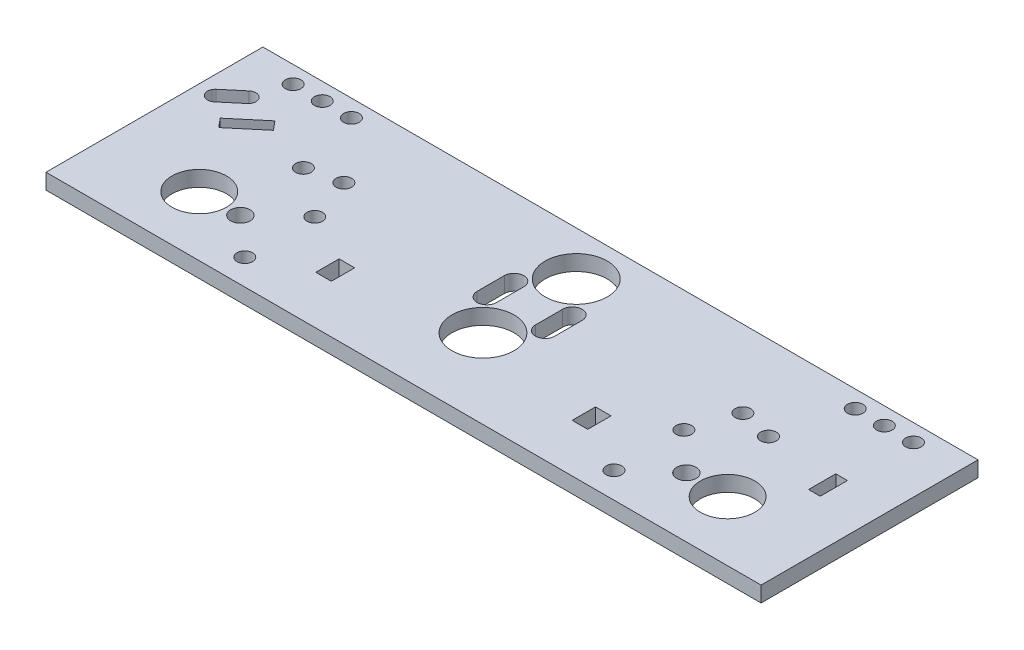
SolidWorks part; units mm, degrees
ref_plane "Front Plane" through (0, 0, 0) normal (0, 0, 1) x (1, 0, 0)
ref_plane "Top Plane" through (0, 0, 0) normal (0, 1, 0) x (1, 0, 0)
ref_plane "Right Plane" through (0, 0, 0) normal (1, 0, 0) x (0, 0, -1)
sketch "Sketch1" plane through (0, 0, 0) normal (0, 1, 0) x (1, 0, 0)
  line L0 (0, 0) -> (0, 59.0825) construction
  line L1 (-7.5, 15.5) -> (-7.5, 8.5) construction
  line L2 (-5, 15.5) -> (-5, 8.5)
  line L3 (-10, 15.5) -> (-10, 8.5)
  line L4 (-7.5, 15.5) -> (-7.5, 24) construction
  line L5 (-7.5, 8.5) -> (-7.5, 0) construction
  line L6 (-92.0307, 35.3895) -> (-92.0307, -20.4445)
  line L7 (-35, -2.0315) -> (-31, -2.0315)
  line L8 (-35, -2.0315) -> (-35, -8.0315)
  line L9 (-35, -8.0315) -> (-31, -8.0315)
  line L10 (-31, -2.0315) -> (-31, -8.0315)
  line L11 (-92.0307, -20.4445) -> (92.0307, -20.4445)
  line L12 (-92.0307, 35.3895) -> (92.0307, 35.3895)
  line L13 (7.5, 15.5) -> (7.5, 8.5) construction
  line L14 (5, 15.5) -> (5, 8.5)
  line L15 (10, 15.5) -> (10, 8.5)
  line L16 (7.5, 8.5) -> (7.5, 0) construction
  line L17 (7.5, 15.5) -> (7.5, 24) construction
  line L18 (31, -2.0315) -> (31, -8.0315)
  line L19 (35, -8.0315) -> (31, -8.0315)
  line L20 (35, -2.0315) -> (35, -8.0315)
  line L21 (35, -2.0315) -> (31, -2.0315)
  line L22 (92.0307, 35.3895) -> (92.0307, -20.4445)
  line L23 (-97.3653, 12) -> (-74.7906, 12) construction
  line L24 (76.8419, 13.9685) -> (79.8419, 13.9685)
  line L25 (76.8419, 13.9685) -> (76.8419, 6.9685)
  line L26 (76.8419, 6.9685) -> (79.8419, 6.9685)
  line L27 (79.8419, 13.9685) -> (79.8419, 6.9685)
  line L28 (-72.0903, 18.1667) -> (-74.0187, 20.4648)
  line L29 (-72.0903, 18.1667) -> (-79.7508, 11.7388)
  line L30 (-79.7508, 11.7388) -> (-81.6791, 14.0369)
  line L31 (-74.0187, 20.4648) -> (-81.6791, 14.0369)
  line L32 (-87.3337, 18.43) -> (-82.7374, 22.2868) construction
  line L33 (-88.6193, 19.9621) -> (-84.023, 23.8189)
  line L34 (-86.0481, 16.898) -> (-81.4519, 20.7547)
  circle A0 centre (0, 24) radius 8
  circle A1 centre (0, 0) radius 8
  arc A2 (-5, 15.5) -> (-10, 15.5) centre (-7.5, 15.5) ccw
  arc A3 (-10, 8.5) -> (-5, 8.5) centre (-7.5, 8.5) ccw
  circle A4 centre (-57.4, -5.0315) radius 2.5
  circle A5 centre (-47.5079, -13.7966) radius 2
  circle A6 centre (-47.5079, 4.2034) radius 2
  circle A7 centre (-59.8623, 13.6321) radius 2
  circle A8 centre (-64.8419, 30.9685) radius 2
  circle A9 centre (-72.3419, 30.9685) radius 2
  circle A10 centre (-79.8419, 30.9685) radius 2
  circle A11 centre (-68, -5.0315) radius 7
  circle A12 centre (-51.3496, 15.5457) radius 2
  arc A13 (5, 15.5) -> (10, 15.5) centre (7.5, 15.5) cw
  arc A14 (10, 8.5) -> (5, 8.5) centre (7.5, 8.5) cw
  circle A15 centre (51.3496, 15.5457) radius 2
  circle A16 centre (68, -5.0315) radius 7
  circle A17 centre (79.8419, 30.9685) radius 2
  circle A18 centre (72.3419, 30.9685) radius 2
  circle A19 centre (64.8419, 30.9685) radius 2
  circle A20 centre (59.8623, 13.6321) radius 2
  circle A21 centre (47.5079, 4.2034) radius 2
  circle A22 centre (47.5079, -13.7966) radius 2
  circle A23 centre (57.4, -5.0315) radius 2.5
  arc A24 (-88.6193, 19.9621) -> (-86.0481, 16.898) centre (-87.3337, 18.43) ccw
  arc A25 (-81.4519, 20.7547) -> (-84.023, 23.8189) centre (-82.7374, 22.2868) ccw
  point P6 (0, 35.3895)
  point P12 (-7.5, 12)
  point P43 (0, -20.4445)
  point P45 (-35, -5.0315)
  point P49 (7.5, 12)
  point P92 (-85.0356, 20.3584)
  dimension "D1" = 8
  dimension "D2" = 5
  dimension "D5" = 4
  dimension "D8" = 5
  dimension "D9" = 14
  dimension "D10" = 6
  dimension "D12" = 10.6
  dimension "D13" = 7
  dimension "D14" = 18
  dimension "D15" = 33
  dimension "D16" = 36
  dimension "24" = 24
  dimension "D3" = 7
  dimension "D4" = 5
  dimension "D6" = 7.5
  dimension "D7" = 7.5
  dimension "D11" = 4
  dimension "D17" = 31
  dimension "D18" = 3
  dimension "D19" = 17
  dimension "D20" = 40
  dimension "D21" = 3
  dimension "D22" = 10
  dimension "D23" = 90
  dimension "D24" = 6
  dimension "D25" = 4
  dimension "D26" = 5
extrude "Boss-Extrude1" add sketch "Sketch1" along normal blind 4
